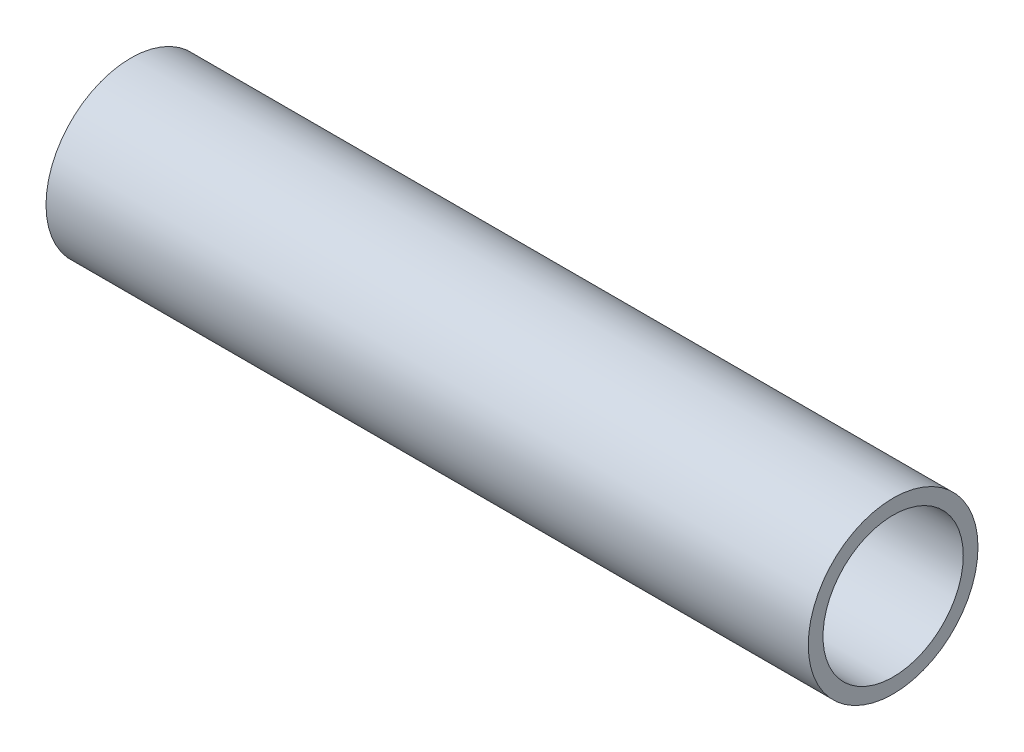
SolidWorks part; units mm, degrees
material "ASTM A106"
ref_plane "Front Plane" through (0, 0, 0) normal (0, 0, 1) x (1, 0, 0)
ref_plane "Top Plane" through (0, 0, 0) normal (0, 1, 0) x (1, 0, 0)
ref_plane "Right Plane" through (0, 0, 0) normal (1, 0, 0) x (0, 0, -1)
sketch "Sketch1" plane through (0, 0, 0) normal (1, 0, 0) x (0, 0, -1)
  circle A0 centre (0, 0) radius 16.7
  circle A1 centre (0, 0) radius 13.8
  dimension "D1" = 33.4
  dimension "D2" = 27.6
extrude "Boss-Extrude1" add sketch "Sketch1" along normal blind 150
